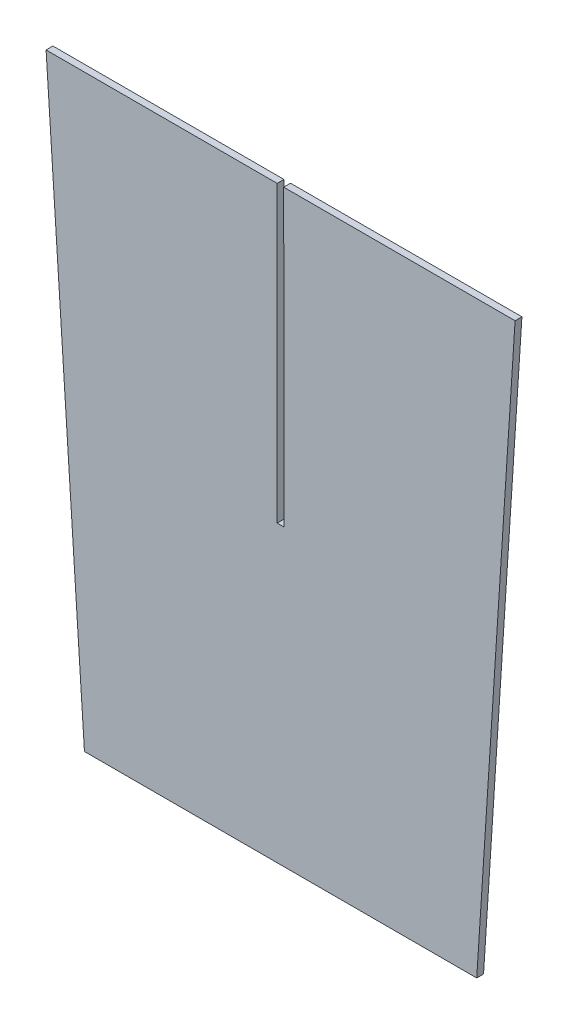
SolidWorks part; units mm, degrees
ref_plane "Front Plane" through (0, 0, 0) normal (0, 0, 1) x (1, 0, 0)
ref_plane "Top Plane" through (0, 0, 0) normal (0, 1, 0) x (1, 0, 0)
ref_plane "Right Plane" through (0, 0, 0) normal (1, 0, 0) x (0, 0, -1)
sketch "Sketch4" plane through (0, 0, 0) normal (0, 0, 1) x (1, 0, 0)
  line L0 (0, 0) -> (230, 0)
  line L1 (115, 0) -> (115, 345)
  line L2 (252.5, 345) -> (-22.5, 345)
  line L3 (-22.5, 345) -> (0, 0)
  line L4 (115, 345) -> (115, -53.3069) construction
  line L5 (252.5, 345) -> (230, 0)
  line L6 (115, 172.5) -> (117, 172.5)
  line L8 (117, 0) -> (113, 0)
  line L10 (113, 172.5) -> (115, 172.5)
  line L11 (113, 172.5) -> (113, 345)
  line L12 (113, 345) -> (120.6483, 345)
  line L14 (117, 172.5) -> (116.8242, 345)
  dimension "D1" = 115
  dimension "D2" = 345
  dimension "D3" = 137.5
  dimension "D4" = 2
  dimension "D5" = 2
extrude "Boss-Extrude1" add sketch "Sketch4" along normal blind 4 contours L5 L2 L1 L0 | L2 L3 L0 L1
